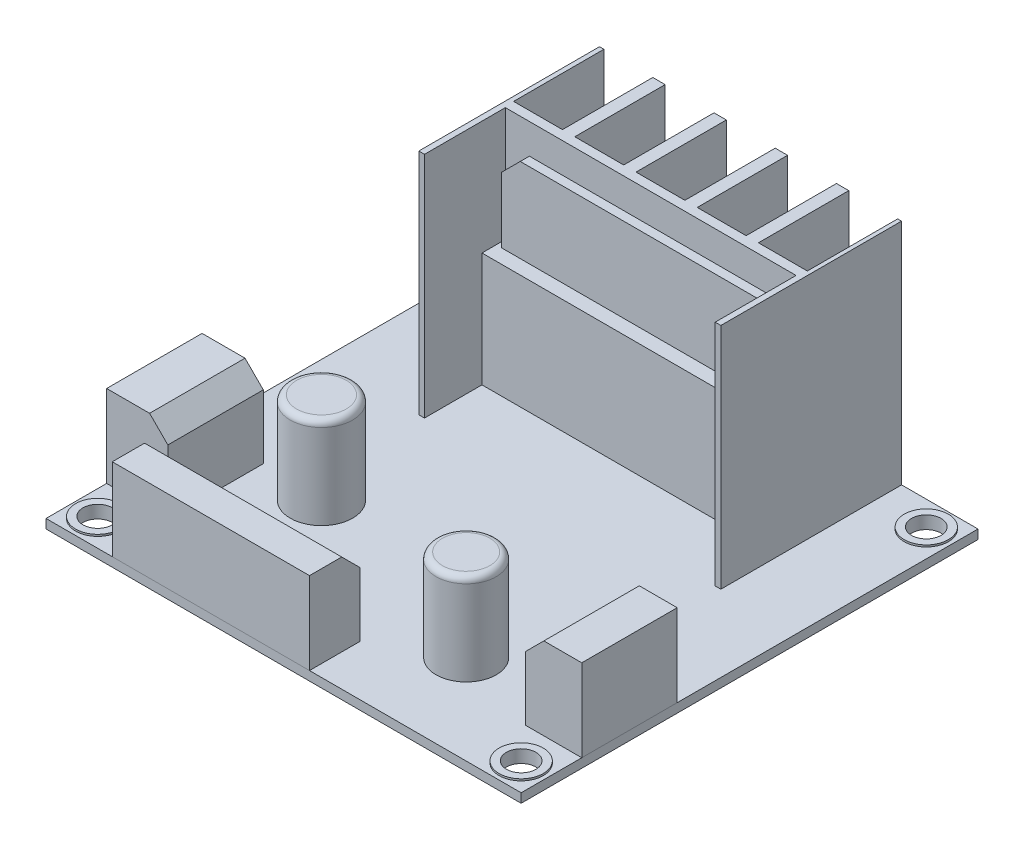
SolidWorks part; units mm, degrees
ref_plane "Front Plane" through (0, 0, 0) normal (0, 0, 1) x (1, 0, 0)
ref_plane "Top Plane" through (0, 0, 0) normal (0, 1, 0) x (1, 0, 0)
ref_plane "Right Plane" through (0, 0, 0) normal (1, 0, 0) x (0, 0, -1)
other "Center of Mass"
sketch "Sketch1" plane through (0, 0, 0) normal (0, 1, 0) x (1, 0, 0)
  line L1 (-26, -25) -> (26, -25)
  line L2 (-26, -25) -> (-26, 25)
  line L3 (-26, 25) -> (26, 25)
  line L4 (26, -25) -> (26, 25)
  line L5 (-26, -25) -> (26, 25) construction
  line L6 (-26, 25) -> (26, -25) construction
  point P0 (0, 0)
  dimension "D1" = 52
  dimension "D2" = 50
extrude "Boss-Extrude1" add sketch "Sketch1" along normal blind 1
sketch "Sketch2" plane through (0, 1, 0) normal (0, 1, 0) x (1, 0, 0)
  line L0 (-26, -25) -> (26, -25) construction
  line L1 (-18.7447, -25) -> (2.8359, -25)
  line L2 (-18.7447, -25) -> (-18.7447, -19.471)
  line L3 (-18.7447, -19.471) -> (2.8359, -19.471)
  line L4 (2.8359, -25) -> (2.8359, -19.471)
  line L5 (-26, 25) -> (-26, -25) construction
  line L6 (-26, -18.3643) -> (-19.298, -18.3643)
  line L7 (-26, -18.3643) -> (-26, -7.9198)
  line L8 (-26, -7.9198) -> (-19.298, -7.9198)
  line L9 (-19.298, -18.3643) -> (-19.298, -7.9198)
  line L10 (26, -25) -> (26, 25) construction
  line L11 (26, -18.3643) -> (19.8514, -18.3643)
  line L12 (26, -18.3643) -> (26, -7.9198)
  line L13 (26, -7.9198) -> (19.8514, -7.9198)
  line L14 (19.8514, -18.3643) -> (19.8514, -7.9198)
extrude "Boss-Extrude2" add sketch "Sketch2" along normal blind 9 separate body
sketch "Sketch3" plane through (0, 1, 0) normal (0, 1, 0) x (1, 0, 0)
  circle A0 centre (-12.6579, -8.1965) radius 3.4174
  circle A1 centre (10.1678, -15.1825) radius 3.2948
extrude "Boss-Extrude3" add sketch "Sketch3" along normal blind 10 separate body
sketch "Sketch4" plane through (0, 1, 0) normal (0, 1, 0) x (1, 0, 0)
  line L0 (0, 25) -> (0, -25) construction
  line L1 (26, 25) -> (-26, 25) construction
  line L2 (-18.7447, -25) -> (2.8359, -25) construction
  line L3 (26, 0) -> (-26, 0) construction
  line L4 (26, -25) -> (26, 25) construction
  line L5 (-26, 25) -> (-26, -25) construction
  circle A0 centre (-23.1715, 22.1685) radius 1.6148
  circle A1 centre (23.1715, 22.1685) radius 1.6148
  circle A2 centre (23.1715, -22.1685) radius 1.6148
  circle A3 centre (-23.1715, -22.1685) radius 1.6148
extrude "Cut-Extrude1" cut sketch "Sketch4" against normal blind 10
sketch "Sketch5" plane through (0, 1, 0) normal (0, 1, 0) x (1, 0, 0)
  line L0 (0, 25) -> (0, -24.7278) construction
  line L1 (26, 25) -> (-26, 25) construction
  line L2 (26, 0) -> (-26, 0) construction
  line L3 (26, -25) -> (26, 25) construction
  line L4 (-26, 25) -> (-26, -25) construction
  circle A0 centre (-23.1715, 22.1685) radius 2.416
  circle A1 centre (23.1715, 22.1685) radius 2.416
  circle A2 centre (23.1715, -22.1685) radius 2.416
  circle A3 centre (-23.1715, -22.1685) radius 2.416
  circle A4 centre (-23.1715, 22.1685) radius 1.6148
  circle A5 centre (23.1715, 22.1685) radius 1.6148
  circle A6 centre (23.1715, -22.1685) radius 1.6148
  circle A7 centre (-23.1715, -22.1685) radius 1.6148
extrude "Boss-Extrude4" add sketch "Sketch5" along normal blind 0.2 and the other way blind 1.2
sketch "Sketch6" plane through (0, 1, 0) normal (0, 1, 0) x (1, 0, 0)
  line L0 (26, 25) -> (-26, 25) construction
  line L1 (-15.4246, 25) -> (17.638, 25)
  line L2 (-15.4246, 25) -> (-15.4246, 5.2222)
  line L3 (-15.4246, 5.2222) -> (17.638, 5.2222)
  line L4 (17.638, 25) -> (17.638, 5.2222)
extrude "Boss-Extrude5" add sketch "Sketch6" along normal blind 25 separate body
sketch "Sketch7" plane through (0, 26, 0) normal (0, 1, 0) x (1, 0, 0)
  line L0 (17.638, 25) -> (-15.4246, 25) construction
  line L1 (-14.9404, 25) -> (-9.5904, 25)
  line L2 (-14.9404, 25) -> (-14.9404, 15.1133)
  line L3 (-14.9404, 15.1133) -> (-9.5904, 15.1133)
  line L4 (-9.5904, 25) -> (-9.5904, 15.1133)
  line L5 (-8.2404, 25) -> (-2.8904, 25)
  line L6 (-8.2404, 25) -> (-8.2404, 15.1133)
  line L7 (-8.2404, 15.1133) -> (-2.8904, 15.1133)
  line L8 (-2.8904, 25) -> (-2.8904, 15.1133)
  line L9 (-1.5404, 25) -> (3.8096, 25)
  line L10 (-1.5404, 25) -> (-1.5404, 15.1133)
  line L11 (-1.5404, 15.1133) -> (3.8096, 15.1133)
  line L12 (3.8096, 25) -> (3.8096, 15.1133)
  line L13 (5.1596, 25) -> (10.5096, 25)
  line L14 (5.1596, 25) -> (5.1596, 15.1133)
  line L15 (5.1596, 15.1133) -> (10.5096, 15.1133)
  line L16 (10.5096, 25) -> (10.5096, 15.1133)
  line L17 (11.8596, 25) -> (17.2096, 25)
  line L18 (11.8596, 25) -> (11.8596, 15.1133)
  line L19 (11.8596, 15.1133) -> (17.2096, 15.1133)
  line L20 (17.2096, 25) -> (17.2096, 15.1133)
  dimension "D2" = 5.35
  dimension "D1" = 5
extrude "Cut-Extrude2" cut sketch "Sketch7" against normal blind 25
sketch "Sketch8" plane through (0, 26, 0) normal (0, 1, 0) x (1, 0, 0)
  line L0 (-15.4246, 5.2222) -> (17.638, 5.2222) construction
  line L1 (-14.8021, 14.0758) -> (17.0155, 14.0758)
  line L2 (-14.8021, 14.0758) -> (-14.8021, 5.2222)
  line L3 (-14.8021, 5.2222) -> (17.0155, 5.2222)
  line L4 (17.0155, 14.0758) -> (17.0155, 5.2222)
extrude "Cut-Extrude3" cut sketch "Sketch8" against normal blind 12.5
sketch "Sketch9" plane through (0, 13.5, 0) normal (0, 1, 0) x (1, 0, 0)
  line L0 (17.0155, 5.2222) -> (17.0155, 14.0758) construction
  line L1 (-14.8021, 5.2222) -> (17.0155, 5.2222)
  line L2 (-14.8021, 5.2222) -> (-14.8021, 11.5166)
  line L3 (-14.8021, 11.5166) -> (17.0155, 11.5166)
  line L4 (17.0155, 5.2222) -> (17.0155, 11.5166)
extrude "Cut-Extrude4" cut sketch "Sketch9" against normal blind 12.5
sketch "Sketch10" plane through (0, 0, -14.0758) normal (0, 0, 1) x (1, 0, 0)
  line L0 (1.1067, 26) -> (1.1067, 13.5) construction
  line L1 (17.0155, 26) -> (-14.8021, 26) construction
  line L2 (17.0155, 13.5) -> (-14.8021, 13.5) construction
  line L3 (-14.2301, 13.5) -> (-14.2301, 20.6543)
  line L4 (-14.2301, 20.6543) -> (-12.1734, 22.711)
  line L5 (-12.1734, 22.711) -> (14.3868, 22.711)
  line L6 (16.4435, 13.5) -> (16.4435, 20.6543)
  line L7 (16.4435, 20.6543) -> (14.3868, 22.711)
  line L8 (-14.2301, 13.5) -> (16.4435, 13.5)
  point P13 (1.1067, 22.711)
extrude "Boss-Extrude6" add sketch "Sketch10" along normal blind 1
fillet "Fillet1" radius 0.7 1 edges at (10.1678, 11, 18.4773)
fillet "Fillet2" radius 0.7 1 edges at (-12.6579, 11, 11.6139)
chamfer "Chamfer1" distance 2 angle 45 1 edges at (19.8514, 10, 13.142)
chamfer "Chamfer2" distance 2 angle 45 1 edges at (-7.9544, 10, 19.471)
chamfer "Chamfer3" distance 2 angle 45 1 edges at (-19.298, 10, 13.142)
